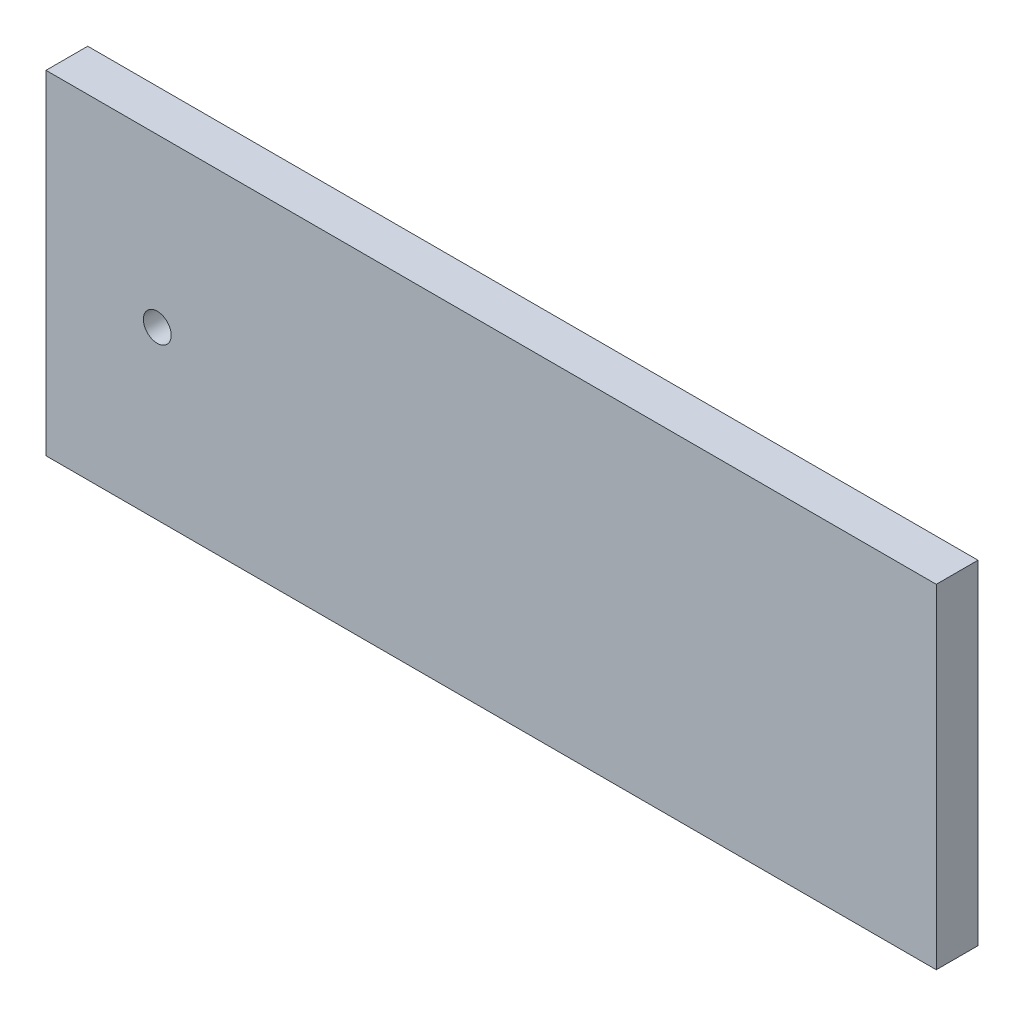
SolidWorks part; units mm, degrees
ref_plane "Front Plane" through (0, 0, 0) normal (0, 0, 1) x (1, 0, 0)
ref_plane "Top Plane" through (0, 0, 0) normal (0, 1, 0) x (1, 0, 0)
ref_plane "Right Plane" through (0, 0, 0) normal (1, 0, 0) x (0, 0, -1)
sketch "Sketch1" plane through (0, 0, 0) normal (0, 0, 1) x (1, 0, 0)
  line L1 (0, 0) -> (101.6, 0)
  line L2 (0, 0) -> (0, 76.2)
  line L3 (0, 76.2) -> (101.6, 76.2)
  line L4 (101.6, 0) -> (101.6, 76.2)
sketch "Sketch2" plane through (0, 0, 0) normal (0, 0, 1) x (1, 0, 0)
  line L1 (0, 0) -> (203.2, 0)
  line L2 (0, 0) -> (0, 76.2)
  line L3 (0, 76.2) -> (203.2, 76.2)
  line L4 (203.2, 0) -> (203.2, 76.2)
extrude "lin_plate" add sketch "Sketch2" along normal blind 9.525
sketch "Sketch3" plane through (0, 0, 0) normal (0, 0, 1) x (1, 0, 0)
  circle A0 centre (25.4, 38.1) radius 3.175
extrude "lp_seed" cut sketch "Sketch3" along normal through all
